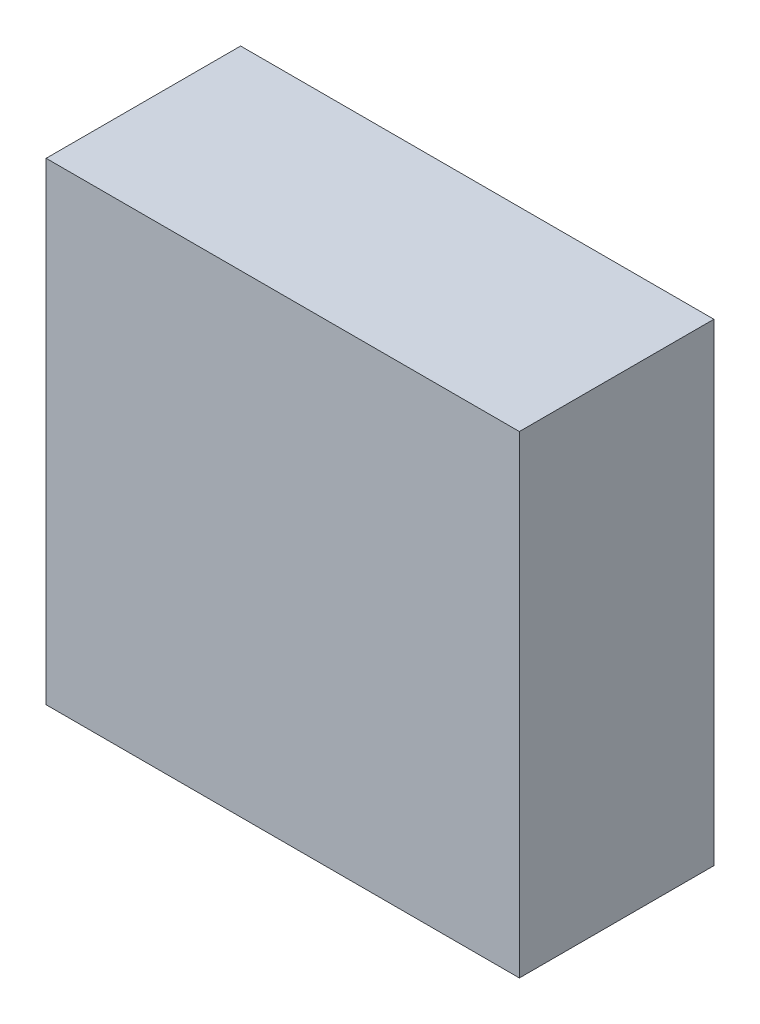
SolidWorks part; units mm, degrees
ref_plane "Front Plane" through (0, 0, 0) normal (0, 0, 1) x (1, 0, 0)
ref_plane "Top Plane" through (0, 0, 0) normal (0, 1, 0) x (1, 0, 0)
ref_plane "Right Plane" through (0, 0, 0) normal (1, 0, 0) x (0, 0, -1)
sketch "Sketch1" plane through (0, 0, 0) normal (0, 1, 0) x (1, 0, 0)
  line L1 (0, 0) -> (185.42, 0)
  line L2 (0, 0) -> (0, 76.2)
  line L3 (0, 76.2) -> (185.42, 76.2)
  line L4 (185.42, 0) -> (185.42, 76.2)
  dimension "D1" = 185.42
  dimension "D2" = 76.2
extrude "Boss-Extrude1" add sketch "Sketch1" along normal blind 185.42
